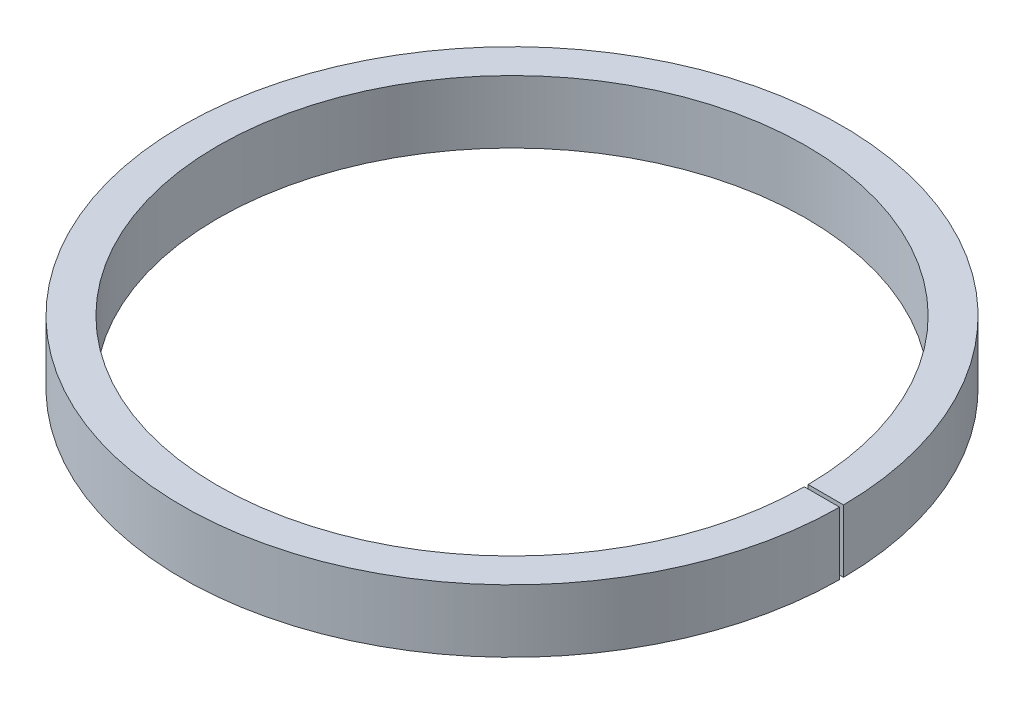
SolidWorks part; units mm, degrees
material "Sponge"
ref_plane "Front Plane" through (0, 0, 0) normal (0, 0, 1) x (1, 0, 0)
ref_plane "Top Plane" through (0, 0, 0) normal (0, 1, 0) x (1, 0, 0)
ref_plane "Right Plane" through (0, 0, 0) normal (1, 0, 0) x (0, 0, -1)
sketch "Sketch1" plane through (0, 0, 0) normal (0, 1, 0) x (1, 0, 0)
  line L0 (37.4992, 0.25) -> (41.9993, 0.25)
  line L1 (37.4992, -0.25) -> (41.9993, -0.25)
  line L2 (37.4992, 0.25) -> (37.4992, -0.25) construction
  line L3 (37.4992, 0) -> (0, 0) construction
  arc A0 (37.4992, 0.25) -> (37.4992, -0.25) centre (0, 0) ccw
  arc A1 (41.9993, 0.25) -> (41.9993, -0.25) centre (0, 0) ccw
  dimension "D1" = 0.5
  dimension "D2" = 37.5
  dimension "D3" = 42
extrude "Boss-Extrude1" add sketch "Sketch1" along normal mid plane 8
